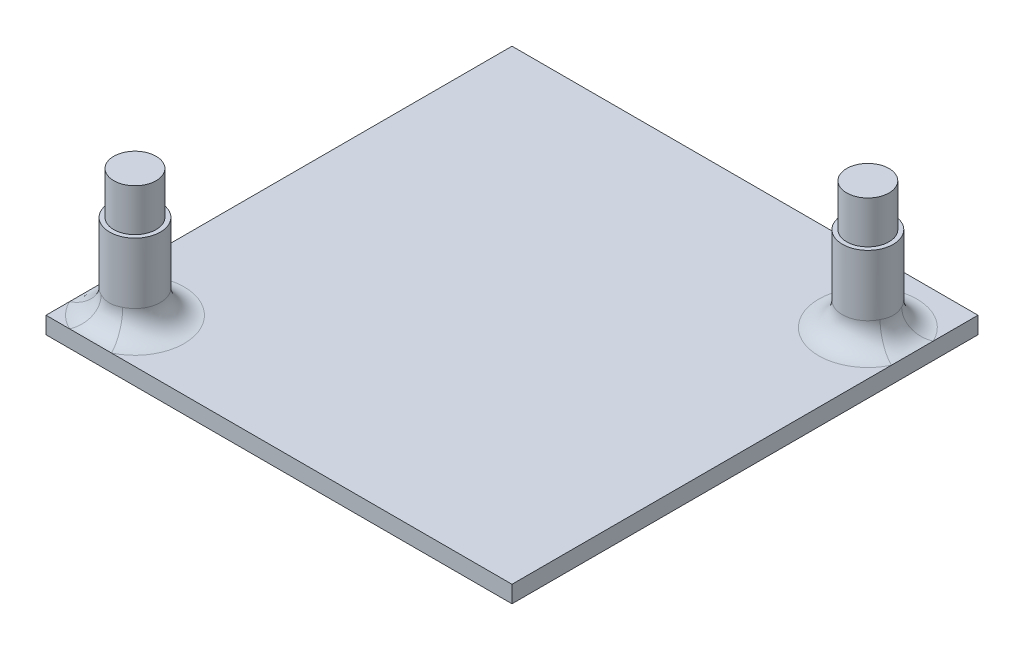
SolidWorks part; units mm, degrees
ref_plane "Front Plane" through (0, 0, 0) normal (0, 0, 1) x (1, 0, 0)
ref_plane "Top Plane" through (0, 0, 0) normal (0, 1, 0) x (1, 0, 0)
ref_plane "Right Plane" through (0, 0, 0) normal (1, 0, 0) x (0, 0, -1)
sketch "Sketch1" plane through (0, 0, 0) normal (0, 1, 0) x (1, 0, 0)
  line L0 (-27.5, 27.5) -> (-27.5, 40)
  line L1 (-27.5, 27.5) -> (27.5, 27.5)
  line L2 (-27.5, 27.5) -> (-27.5, -27.5)
  line L3 (-27.5, -27.5) -> (27.5, -27.5)
  line L4 (27.5, 27.5) -> (27.5, -27.5)
  line L5 (-27.5, 27.5) -> (27.5, -27.5) construction
  line L6 (-27.5, -27.5) -> (27.5, 27.5) construction
  line L7 (-27.5, 40) -> (52.5, 40)
  line L8 (-27.5, -27.5) -> (-27.5, -40)
  line L9 (-27.5, -40) -> (52.5, -40)
  line L10 (52.5, 40) -> (52.5, -40)
  line L11 (-27.5, -40) -> (-27.5, -27.5)
  circle A0 centre (22.25, -19.75) radius 2.5 construction
  circle A1 centre (-22.25, 22.25) radius 2.5 construction
  point P0 (0, 0)
  point P14 (52.5, 0)
  dimension "D5" = 5
  dimension "D1" = 55
  dimension "D2" = 5.25
  dimension "D3" = 19.75
  dimension "D4" = 5.25
  dimension "D6" = 80
  dimension "D7" = 80
extrude "Boss-Extrude1" add sketch "Sketch1" along normal blind 2 contours L4 L1 L2 L3
sketch "Sketch2" plane through (0, 2, 0) normal (0, 1, 0) x (1, 0, 0)
  circle A0 centre (-22.25, -22.25) radius 3
  circle A1 centre (22.25, 19.75) radius 3
  dimension "D5" = 6
  dimension "D6" = 6
  dimension "D1" = 22.25
  dimension "D2" = 19.75
  dimension "D3" = 22.25
  dimension "D4" = 22.25
extrude "Boss-Extrude2" add sketch "Sketch2" along normal blind 10
fillet "Fillet1" radius 2.8 2 edges at (-22.25, 2, 25.25) (22.25, 2, -16.75)
sketch "Sketch3" plane through (0, 12, 0) normal (0, 1, 0) x (1, 0, 0)
  circle A0 centre (-22.25, -22.25) radius 2.5
  circle A1 centre (22.25, 19.75) radius 2.5
  dimension "D1" = 5
extrude "Boss-Extrude3" add sketch "Sketch3" along normal blind 5
